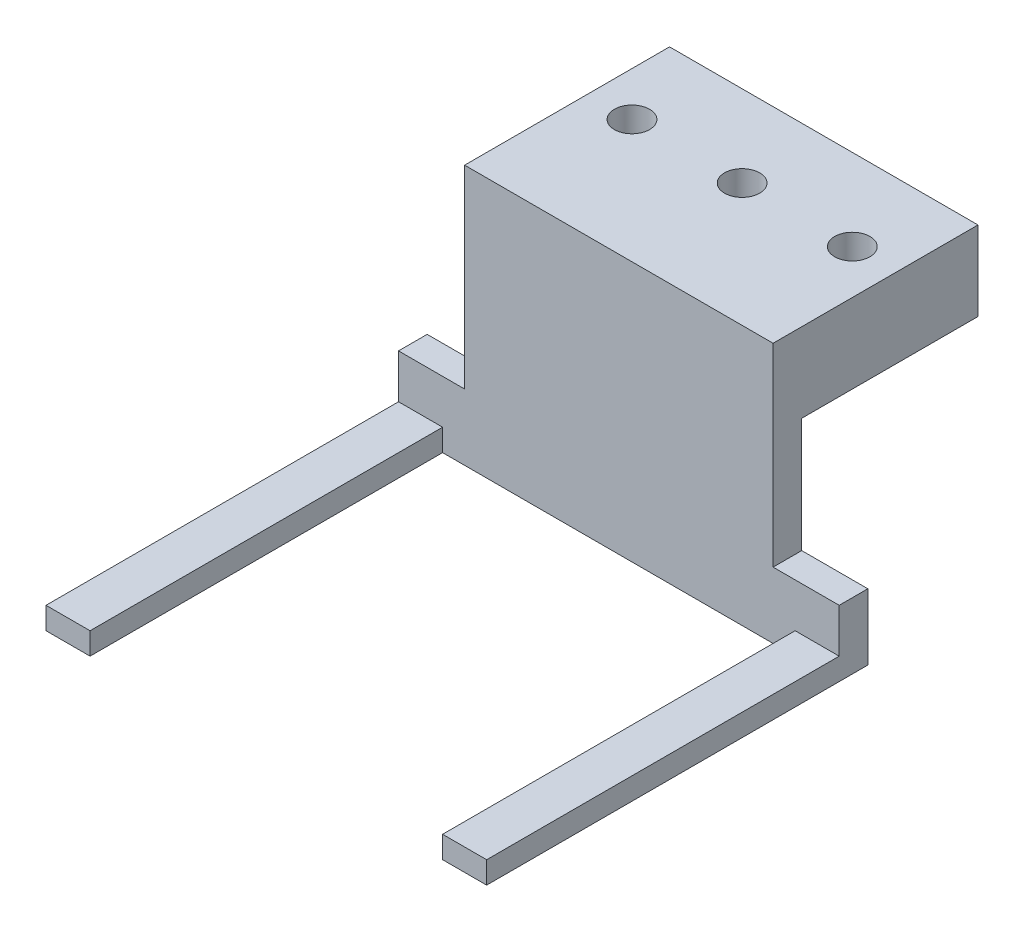
SolidWorks part; units mm, degrees
ref_plane "前视基准面" through (0, 0, 0) normal (0, 0, 1) x (1, 0, 0)
ref_plane "上视基准面" through (0, 0, 0) normal (0, 1, 0) x (1, 0, 0)
ref_plane "右视基准面" through (0, 0, 0) normal (1, 0, 0) x (0, 0, -1)
other "Configuration Table"
sketch "草图1" plane through (0, 0, 0) normal (0, 1, 0) x (1, 0, 0)
  line L0 (0, 0) -> (0, -40)
  line L1 (0, -40) -> (70, -40)
  line L2 (70, -40) -> (70, 0)
  line L3 (70, 0) -> (0, 0)
  dimension "D1" = 70
  dimension "D2" = 40
extrude "凸台-拉伸1" add sketch "草图1" along normal blind 18
sketch "草图3" plane through (0, 18, 0) normal (0, 1, 0) x (1, 0, 0)
  line L0 (0, -40) -> (0, -46.5)
  line L1 (0, -46.5) -> (70, -46.5)
  line L2 (70, -46.5) -> (70, -40)
  line L3 (0, -40) -> (70, -40)
  dimension "D1" = 6.5
extrude "凸台-拉伸2" add sketch "草图3" against normal blind 59
sketch "草图4" plane through (0, 0, 46.5) normal (0, 0, 1) x (1, 0, 0)
  line L0 (0, -41) -> (-15, -41)
  line L1 (-15, -41) -> (-15, -26)
  line L2 (-15, -26) -> (0, -26)
  line L3 (0, -41) -> (0, 18) construction
  line L4 (0, -26) -> (0, -41)
  dimension "D1" = 15
  dimension "D2" = 15
extrude "凸台-拉伸3" add sketch "草图4" against normal up to surface (6.5 mm away) up to face at (35, -20.5, 40)
ref_plane "基准面1" through (35, 0, 0) normal (1, 0, 0) x (0, 0, -1)
mirror "镜向1" about plane through (35, 0, 0) normal (1, 0, 0) of "凸台-拉伸3"
sketch "草图5" plane through (0, 0, 46.5) normal (0, 0, 1) x (1, 0, 0)
  line L0 (-15, -36) -> (-5, -36)
  line L1 (-15, -26) -> (-15, -41) construction
  line L2 (-5, -36) -> (-5, -41)
  line L3 (-15, -41) -> (85, -41) construction
  line L4 (-5, -41) -> (-15, -41)
  line L5 (-15, -41) -> (-15, -36)
  dimension "D1" = 5
  dimension "D2" = 10
extrude "凸台-拉伸4" add sketch "草图5" along normal blind 80
mirror "镜向2" about plane through (35, 0, 0) normal (1, 0, 0) of "凸台-拉伸4"
sketch "草图7" plane through (0, 18, 0) normal (0, 1, 0) x (1, 0, 0)
  line L2 (70, -46.5) -> (70, 0) construction
  line L3 (35, -46.5) -> (35, 0) construction
  line L4 (0, -46.5) -> (70, -46.5) construction
  line L5 (70, 0) -> (0, 0) construction
  circle A0 centre (35, -18.523) radius 4
  circle A1 centre (60, -18.523) radius 4
  circle A2 centre (10, -18.523) radius 4
  point P0 (0, 0)
  dimension "D1" = 10
  dimension "D2" = 18.523
  dimension "D3" = 18.523
extrude "切除-拉伸1" cut sketch "草图7" against normal up to surface (18 mm away) up to face at (35, 0, 20)
